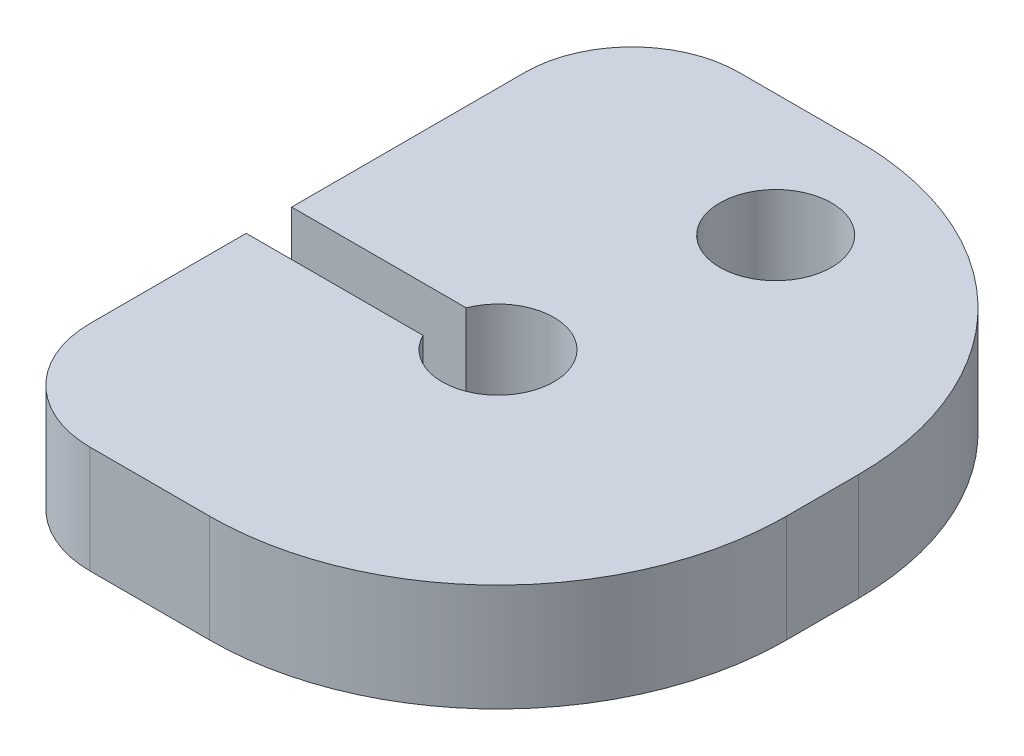
SolidWorks part; units mm, degrees
ref_plane "Front Plane" through (0, 0, 0) normal (0, 0, 1) x (1, 0, 0)
ref_plane "Top Plane" through (0, 0, 0) normal (0, 1, 0) x (1, 0, 0)
ref_plane "Right Plane" through (0, 0, 0) normal (1, 0, 0) x (0, 0, -1)
sketch "Sketch1" plane through (0, 0, 0) normal (0, 1, 0) x (1, 0, 0)
  line L1 (-25.4, 11.43) -> (25.4, 11.43)
  line L2 (-25.4, 11.43) -> (-25.4, -11.43)
  line L3 (-25.4, -11.43) -> (25.4, -11.43)
  line L4 (25.4, 11.43) -> (25.4, -11.43)
  dimension "D1" = 22.86
  dimension "D2" = 50.8
  dimension "D3" = 11.43
  dimension "D4" = 25.4
extrude "Boss-Extrude1" add sketch "Sketch1" along normal blind 3.175
fillet "Fillet1" radius 10.16 2 edges at (-25.4, 1.5875, 11.43) (25.4, 1.5875, 11.43)
sketch "Sketch3" plane through (0, 3.175, 0) normal (0, 1, 0) x (1, 0, 0)
  line L0 (-7.7526, -1.27) -> (18.5521, -1.27) construction
  circle A0 centre (15.24, -1.27) radius 1.9685
  circle A1 centre (16.637, 7.112) radius 1.9685
  arc A2 (15.24, -11.43) -> (25.4, -1.27) centre (15.24, -1.27) ccw construction
  circle A3 centre (-3.81, -1.27) radius 1.9685
  dimension "D1" = 3.937
  dimension "D2" = 3.937
  dimension "D6" = 3.937
  dimension "D3" = 1.397
  dimension "D4" = 8.382
  dimension "D5" = 19.05
extrude "Cut-Extrude1" cut sketch "Sketch3" against normal through all
fillet "Fillet3" radius 10.16 2 edges at (-25.4, 1.5875, -11.43) (25.4, 1.5875, -11.43)
scale "Scale1" scale about centroid uniform scaling no x scale factor 0.84 y scale factor 1 z scale factor 0.84
sketch "Sketch4" plane through (0, 0, 0) normal (0, -1, 0) x (-1, 0, 0)
  line L0 (-6.0432, -9.6098) -> (-6.0432, 9.5926)
  line L1 (12.8544, -9.6098) -> (-12.7488, -9.6098) construction
  line L2 (-12.7488, 9.5926) -> (12.8544, 9.5926) construction
  line L4 (21.3888, 1.0582) -> (21.3888, -1.0754) construction
  line L5 (-6.0432, -9.6098) -> (21.3888, -9.6098)
  line L6 (-21.2832, -1.0754) -> (-21.2832, 1.0582) construction
  line L7 (-6.0432, 9.5926) -> (21.3888, 9.5926)
  line L8 (21.3888, -9.6098) -> (21.3888, 9.5926)
  dimension "D1" = 15.24
extrude "Cut-Extrude2" cut sketch "Sketch4" against normal through all contours L0 L7 L8 L5
fillet "Fillet4" radius 3.175 2 edges at (6.0432, 1.5875, 9.6098) (6.0432, 1.5875, -9.5926)
sketch "Sketch5" plane through (0, 0, 0) normal (0, -1, 0) x (1, 0, 0)
  line L1 (12.9848, 1.8203) -> (6.0432, 1.8203)
  line L2 (6.0432, 1.8203) -> (6.0432, 0.4754)
  line L3 (6.0432, 0.4754) -> (12.9848, 0.4754)
  line L4 (12.9848, 1.8203) -> (12.9848, 0.4754)
  line L5 (6.0432, 6.4348) -> (6.0432, -6.4176) construction
  dimension "D1" = 1.3449
extrude "Cut-Extrude3" cut sketch "Sketch5" against normal through all contours L4 L3 L2 L1
equation "\"D4@Sketch1\"=\"D2@Sketch1\"/2"
equation "\"D3@Sketch1\"=\"D1@Sketch1\"/2"
